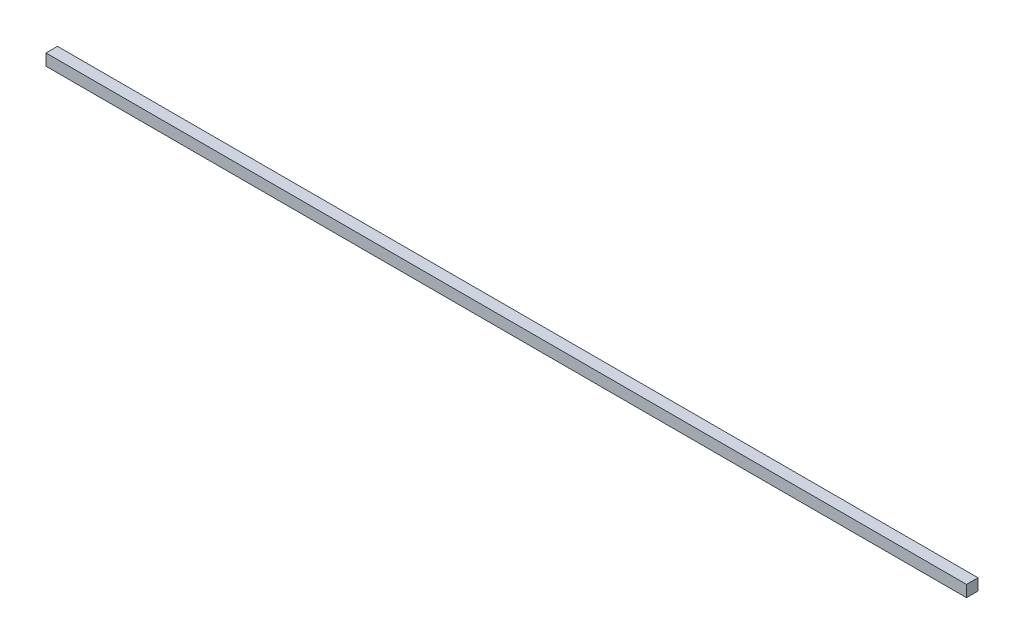
SolidWorks part; units mm, degrees
ref_plane "Front Plane" through (0, 0, 0) normal (0, 0, 1) x (1, 0, 0)
ref_plane "Top Plane" through (0, 0, 0) normal (0, 1, 0) x (1, 0, 0)
ref_plane "Right Plane" through (0, 0, 0) normal (1, 0, 0) x (0, 0, -1)
other "Configuration Table"
sketch "Sketch1" plane through (0, 0, 0) normal (1, 0, 0) x (0, 0, -1)
  line L1 (62.5, -62.5) -> (-62.5, -62.5)
  line L2 (62.5, -62.5) -> (62.5, 62.5)
  line L3 (62.5, 62.5) -> (-62.5, 62.5)
  line L4 (-62.5, -62.5) -> (-62.5, 62.5)
  line L5 (62.5, -62.5) -> (-62.5, 62.5) construction
  line L6 (62.5, 62.5) -> (-62.5, -62.5) construction
  point P0 (0, 0)
  dimension "D1" = 125
  dimension "D2" = 125
extrude "Extrude1" add sketch "Sketch1" along normal blind 10000
